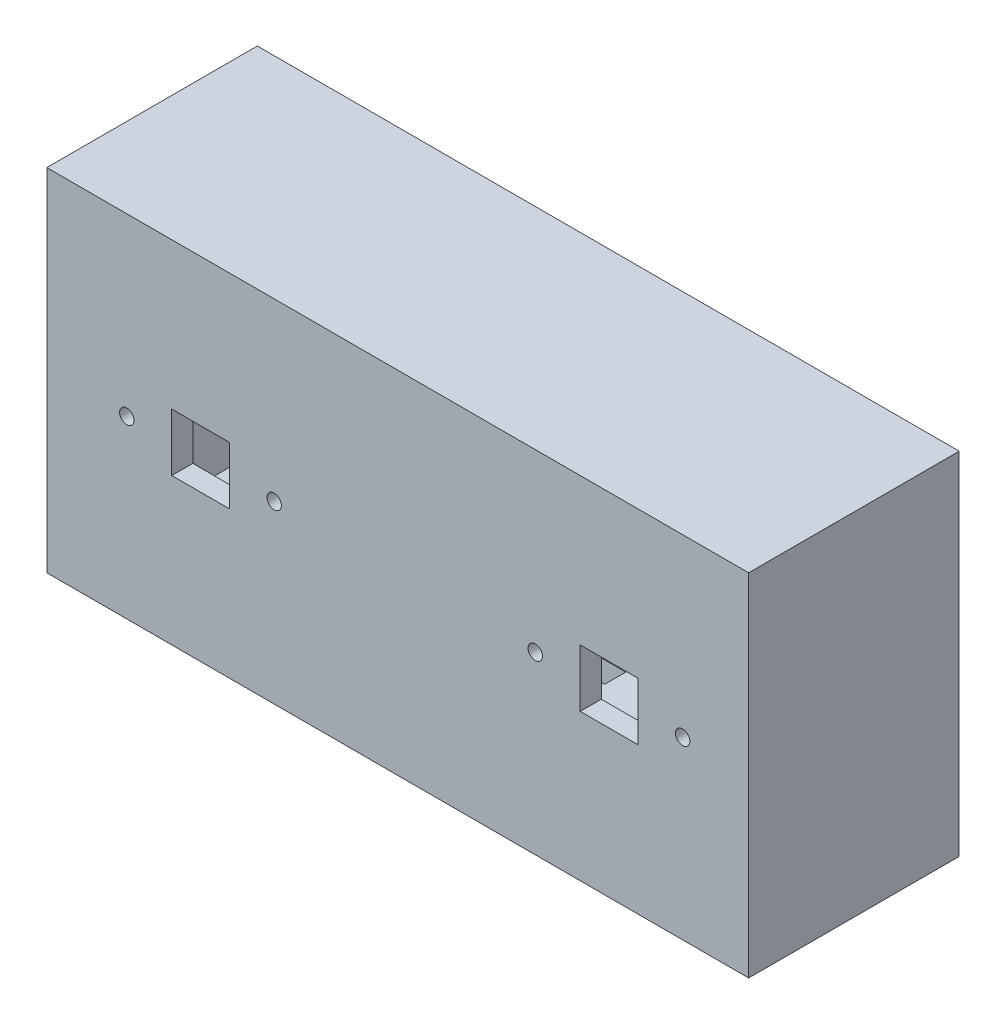
SolidWorks part; units mm, degrees
material "ABS"
ref_plane "Front Plane" through (0, 0, 0) normal (0, 0, 1) x (1, 0, 0)
ref_plane "Top Plane" through (0, 0, 0) normal (0, 1, 0) x (1, 0, 0)
ref_plane "Right Plane" through (0, 0, 0) normal (1, 0, 0) x (0, 0, -1)
sketch "Sketch1" plane through (0, 0, 0) normal (0, 1, 0) x (1, 0, 0)
  line L1 (0, 0) -> (100, 0)
  line L2 (0, 0) -> (0, 30)
  line L3 (0, 30) -> (100, 30)
  line L4 (100, 0) -> (100, 30)
  dimension "D1" = 100
  dimension "D2" = 30
extrude "Boss-Extrude1" add sketch "Sketch1" along normal blind 50
shell "Shell1" thickness 3
sketch "Sketch2" plane through (0, 3, 0) normal (0, 1, 0) x (1, 0, 0)
  line L0 (97, 3) -> (97, 30) construction
  line L1 (65.4, 5.9) -> (42.9, 5.9)
  line L2 (65.4, 5.9) -> (65.4, 18.1)
  line L3 (65.4, 18.1) -> (42.9, 18.1)
  line L4 (42.9, 5.9) -> (42.9, 18.1)
  line L7 (97, 30) -> (3, 30) construction
  point P4 (49, 12)
  dimension "D1" = 22.5
  dimension "D2" = 12.2
  dimension "D3" = 6.1
  dimension "D4" = 6.1
  dimension "D5" = 48
  dimension "D6" = 18
extrude "Cut-Extrude1" cut sketch "Sketch2" against normal up to next
hole_wizard "Ø2.2 (2.2) Diameter Hole1" positions "Sketch3" profile "Sketch4" hole size "Ø2.2" standard "ANSI Metric"
sketch "Sketch3" plane through (0, 3, 0) normal (0, 1, 0) x (1, 0, 0)
  line L0 (65.4, 5.9) -> (65.4, 18.1) construction
  line L1 (42.9, 18.1) -> (42.9, 5.9) construction
  line L2 (65.4, 18.1) -> (42.9, 18.1) construction
  point P0 (68.055, 12)
  point P2 (40.245, 12)
  dimension "D1" = 2.655
  dimension "D2" = 2.655
  dimension "D3" = 6.1
  dimension "D4" = 6.1
sketch "Sketch4" plane through (68.055, 3, -12) normal (1, 0, 0) x (0, 0, 1)
  line L0 (0, 0) -> (0, 3)
  line L1 (0, 3) -> (1.1, 3)
  line L2 (1.1, 3) -> (1.1, 0)
  line L5 (1.1, 0) -> (0, 0)
  line L11 (0, -6.35) -> (0, 107.95) construction
  dimension "Thru Hole Dia." = 2.2
  dimension "Thru Hole Depth" = 3
sketch "Sketch5" plane through (0, 3, 0) normal (0, 1, 0) x (1, 0, 0)
  line L0 (97, 3) -> (97, 30) construction
  line L1 (41.5, 23) -> (56.5, 23)
  line L2 (41.5, 23) -> (41.5, 26)
  line L3 (41.5, 26) -> (56.5, 26)
  line L4 (56.5, 23) -> (56.5, 26)
  line L5 (97, 30) -> (3, 30) construction
  dimension "D1" = 15
  dimension "D2" = 3
  dimension "D3" = 40.5
  dimension "D4" = 4
extrude "Cut-Extrude2" cut sketch "Sketch5" against normal up to next
sketch "Sketch6" plane through (0, 0, 0) normal (0, 0, 1) x (1, 0, 0)
  line L0 (3, 47) -> (3, 3) construction
  line L1 (84.2, 29.1) -> (76, 29.1)
  line L2 (84.2, 29.1) -> (84.2, 20.9)
  line L3 (84.2, 20.9) -> (76, 20.9)
  line L4 (76, 29.1) -> (76, 20.9)
  line L5 (26, 29.1) -> (17.8, 29.1)
  line L6 (26, 29.1) -> (26, 20.9)
  line L7 (26, 20.9) -> (17.8, 20.9)
  line L8 (17.8, 29.1) -> (17.8, 20.9)
  line L9 (0, 0) -> (100, 0) construction
  point P10 (21.9, 20.9)
  dimension "D1" = 8.2
  dimension "D2" = 8.2
  dimension "D3" = 8.2
  dimension "D4" = 8.2
  dimension "D5" = 50
  dimension "D6" = 14.8
  dimension "D7" = 20.9
  dimension "D8" = 20.9
extrude "Cut-Extrude3" cut sketch "Sketch6" against normal up to next
hole_wizard "Ø2.05 (2.05) Diameter Hole1" positions "Sketch7" profile "Sketch8" hole size "Ø2.05" standard "ANSI Metric" end condition through all
sketch "Sketch7" plane through (0, 0, -3) normal (0, 0, -1) x (-1, 0, 0)
  line L0 (-84.2, 20.9) -> (-84.2, 29.1) construction
  line L2 (-76, 29.1) -> (-76, 20.9) construction
  line L3 (-84.2, 29.1) -> (-76, 29.1) construction
  line L4 (-26, 20.9) -> (-26, 29.1) construction
  line L6 (-26, 29.1) -> (-17.8, 29.1) construction
  line L7 (-17.8, 29.1) -> (-17.8, 20.9) construction
  point P0 (-90.6, 25)
  point P2 (-69.6, 25)
  point P4 (-32.4, 25)
  point P6 (-11.4, 25)
  dimension "D1" = 21
  dimension "D2" = 6.4
  dimension "D3" = 6.4
  dimension "D4" = 4.1
  dimension "D5" = 4.1
  dimension "D6" = 21
  dimension "D7" = 6.4
  dimension "D8" = 4.1
  dimension "D9" = 4.1
  dimension "D10" = 6.4
sketch "Sketch8" plane through (90.6, 25, -3) normal (1, 0, 0) x (0, 1, 0)
  line L0 (0, 0) -> (0, 3)
  line L1 (0, 3) -> (1.025, 3)
  line L2 (1.025, 3) -> (1.025, 0)
  line L5 (1.025, 0) -> (0, 0)
  line L11 (0, -6.35) -> (0, 107.95) construction
  dimension "Thru Hole Dia." = 2.05
  dimension "Thru Hole Depth" = 3
sketch "Sketch9" plane through (0, 3, 0) normal (0, 1, 0) x (1, 0, 0)
  line L0 (42.9, 18.1) -> (42.9, 5.9) construction
  line L1 (42.9, 5.9) -> (65.4, 5.9) construction
  circle A0 centre (49, 12) radius 6.1
  dimension "D1" = 6.1
  dimension "D2" = 6.1
